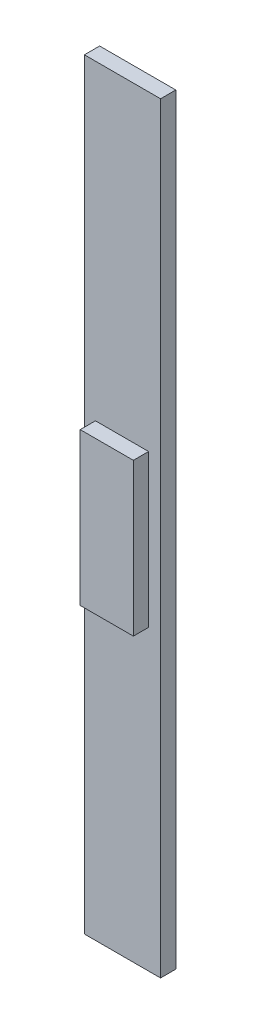
SolidWorks part; units mm, degrees
ref_plane "Front Plane" through (0, 0, 0) normal (0, 0, 1) x (1, 0, 0)
ref_plane "Top Plane" through (0, 0, 0) normal (0, 1, 0) x (1, 0, 0)
ref_plane "Right Plane" through (0, 0, 0) normal (1, 0, 0) x (0, 0, -1)
sketch "Sketch1" plane through (0, 0, 0) normal (0, 0, 1) x (1, 0, 0)
  line L1 (0, 0) -> (1270, 0)
  line L2 (0, 0) -> (0, 12700)
  line L3 (0, 12700) -> (1270, 12700)
  line L4 (1270, 0) -> (1270, 12700)
  dimension "D1" = 1270
  dimension "D2" = 12700
extrude "Boss-Extrude1" add sketch "Sketch1" along normal blind 254
sketch "Sketch2" plane through (0, 0, 254) normal (0, 0, 1) x (1, 0, 0)
  line L1 (184.1236, 7505.0959) -> (1070.3732, 7505.0959)
  line L2 (184.1236, 7505.0959) -> (184.1236, 4965.0959)
  line L3 (184.1236, 4965.0959) -> (1070.3732, 4965.0959)
  line L4 (1070.3732, 7505.0959) -> (1070.3732, 4965.0959)
  dimension "D1" = 2540
extrude "Boss-Extrude2" add sketch "Sketch2" along normal blind 254
equation "\"A\" = 50"
equation "\"B\" = 500"
equation "\"C\"= 10"
equation "\"D\"= \"C\" + 10"
equation "\"D1@Sketch1\"=\"A\""
equation "\"D2@Sketch1\"=\"B\""
equation "\"D1@Boss-Extrude1\"=\"C\""
equation "\"E\"=100"
equation "\"D1@Sketch2\"=\"E\""
equation "\"D1@Boss-Extrude2\"=\"D1@Boss-Extrude1\""
